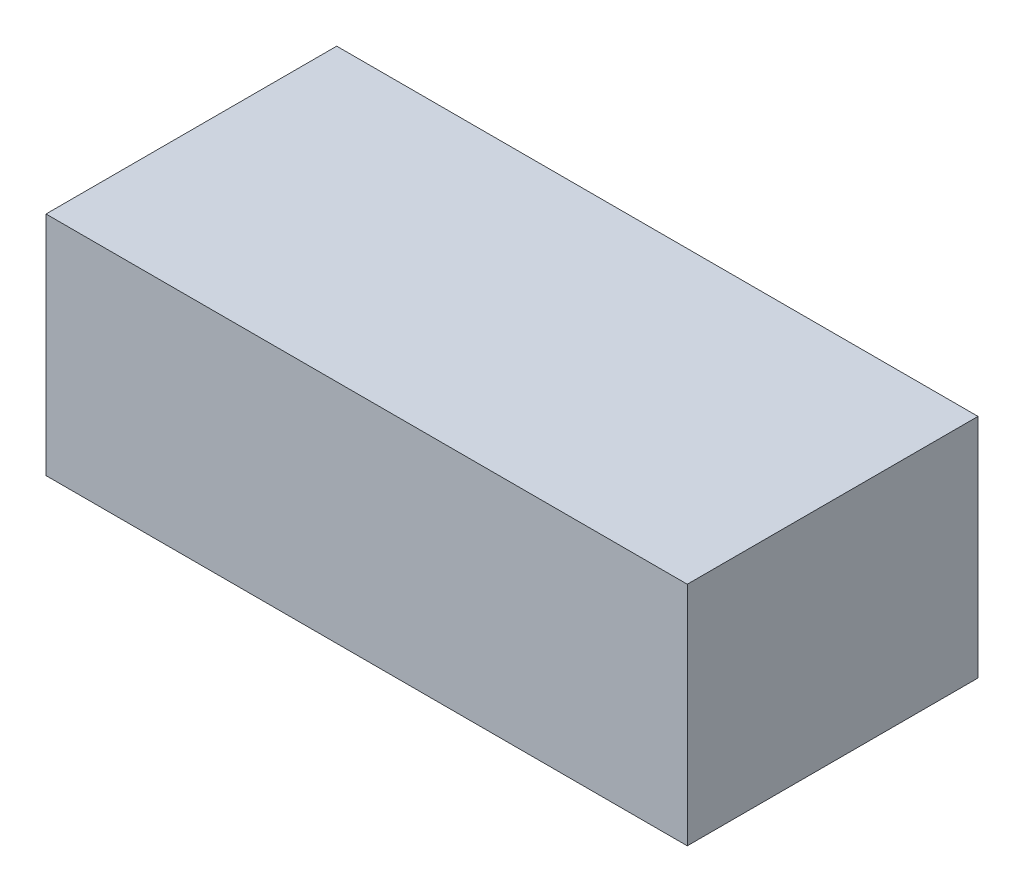
SolidWorks part; units mm, degrees
ref_plane "Front Plane" through (0, 0, 0) normal (0, 0, 1) x (1, 0, 0)
ref_plane "Top Plane" through (0, 0, 0) normal (0, 1, 0) x (1, 0, 0)
ref_plane "Right Plane" through (0, 0, 0) normal (1, 0, 0) x (0, 0, -1)
sketch "Sketch2" plane through (0, 0, 0) normal (0, 1, 0) x (1, 0, 0)
  line L1 (-25.6689, 15.5364) -> (49.3311, 15.5364)
  line L2 (-25.6689, 15.5364) -> (-25.6689, -18.4636)
  line L3 (-25.6689, -18.4636) -> (49.3311, -18.4636)
  line L4 (49.3311, 15.5364) -> (49.3311, -18.4636)
  dimension "D1" = 34
  dimension "D2" = 75
extrude "battery" add sketch "Sketch2" along normal blind 26.5
